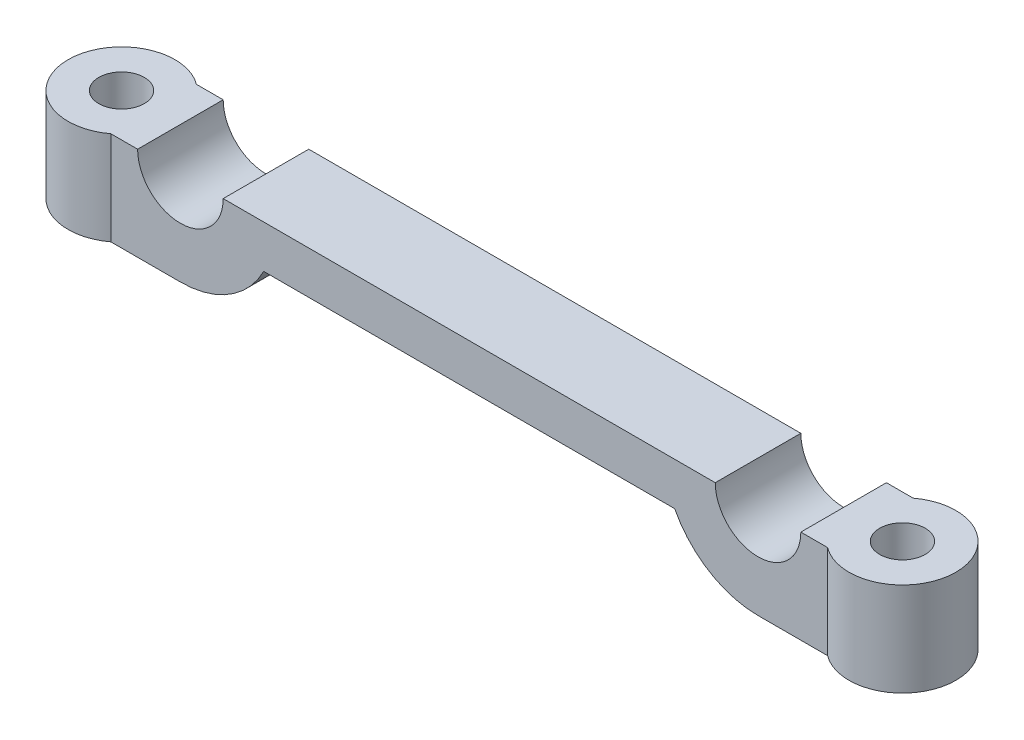
SolidWorks part; units mm, degrees
material "6061 Alloy"
ref_plane "Front Plane" through (0, 0, 0) normal (0, 0, 1) x (1, 0, 0)
ref_plane "Top Plane" through (0, 0, 0) normal (0, 1, 0) x (1, 0, 0)
ref_plane "Right Plane" through (0, 0, 0) normal (1, 0, 0) x (0, 0, -1)
sketch "Sketch1" plane through (0, 0, 0) normal (0, 1, 0) x (1, 0, 0)
  line L1 (-53.1812, 6.35) -> (53.1813, 6.35)
  line L3 (-53.1812, -6.35) -> (53.1813, -6.35)
  line L5 (-53.1812, 6.35) -> (53.1813, -6.35) construction
  line L6 (-53.1812, -6.35) -> (53.1813, 6.35) construction
  arc A0 (-53.1812, 6.35) -> (-53.1812, -6.35) centre (-57.9438, 0) ccw
  arc A1 (53.1813, 6.35) -> (53.1813, -6.35) centre (57.9438, 0) cw
  point P0 (0, 0)
  dimension "D3" = 7.9375
  dimension "D1" = 106.3625
  dimension "D2" = 12.7
extrude "Boss-Extrude1" add sketch "Sketch1" along normal blind 13.8989
sketch "Sketch2" plane through (0, 0, 6.35) normal (0, 0, 1) x (1, 0, 0)
  line L0 (-53.1812, 13.8989) -> (53.1813, 13.8989) construction
  line L2 (0, 13.8989) -> (0, 0) construction
  line L3 (-53.1812, 0) -> (53.1813, 0) construction
  line L4 (-49.2125, 13.8989) -> (-36.5125, 13.8989)
  line L5 (36.5125, 13.8989) -> (49.2125, 13.8989)
  arc A0 (-49.2125, 13.8989) -> (-36.5125, 13.8989) centre (-42.8625, 13.8989) ccw
  arc A1 (49.2125, 13.8989) -> (36.5125, 13.8989) centre (42.8625, 13.8989) cw
  dimension "D1" = 6.35
  dimension "D2" = 3.9688
extrude "Cut-Extrude1" cut sketch "Sketch2" against normal through all and the other way through all
sketch "Sketch3" plane through (0, 0, -6.35) normal (0, 0, -1) x (-1, 0, 0)
  line L0 (-53.1813, 0) -> (53.1812, 0) construction
  line L1 (0, 0) -> (0, 7.5489) construction
  line L2 (30.499, 7.5489) -> (-30.499, 7.5489)
  line L3 (-36.5125, 13.8989) -> (36.5125, 13.8989) construction
  line L4 (42.8625, 0) -> (-42.8625, 0)
  arc A0 (42.8625, 0) -> (30.499, 7.5489) centre (42.8625, 13.8989) cw
  arc A1 (-42.8625, 0) -> (-30.499, 7.5489) centre (-42.8625, 13.8989) ccw
  arc A2 (36.5125, 13.8989) -> (49.2125, 13.8989) centre (42.8625, 13.8989) ccw construction
  dimension "D1" = 6.35
extrude "Cut-Extrude2" cut sketch "Sketch3" against normal through all
hole_wizard "1/4 Clearance Hole1" positions "Sketch4" profile "Sketch5" hole size "1/4" standard "ANSI Inch" end condition through all
sketch "Sketch4" plane through (0, 0, 0) normal (0, -1, 0) x (-1, 0, 0)
  point P0 (57.9438, 0)
  point P3 (-57.9438, 0)
sketch "Sketch5" plane through (-57.9438, 0, 0) normal (1, 0, 0) x (0, 0, -1)
  line L0 (0, 0) -> (0, 13.8989)
  line L1 (0, 13.8989) -> (3.3782, 13.8989)
  line L2 (3.3782, 13.8989) -> (3.3782, 0)
  line L5 (3.3782, 0) -> (0, 0)
  line L11 (0, -6.35) -> (0, 107.95) construction
  dimension "Thru Hole Dia." = 6.7564
  dimension "Thru Hole Depth" = 13.8989
